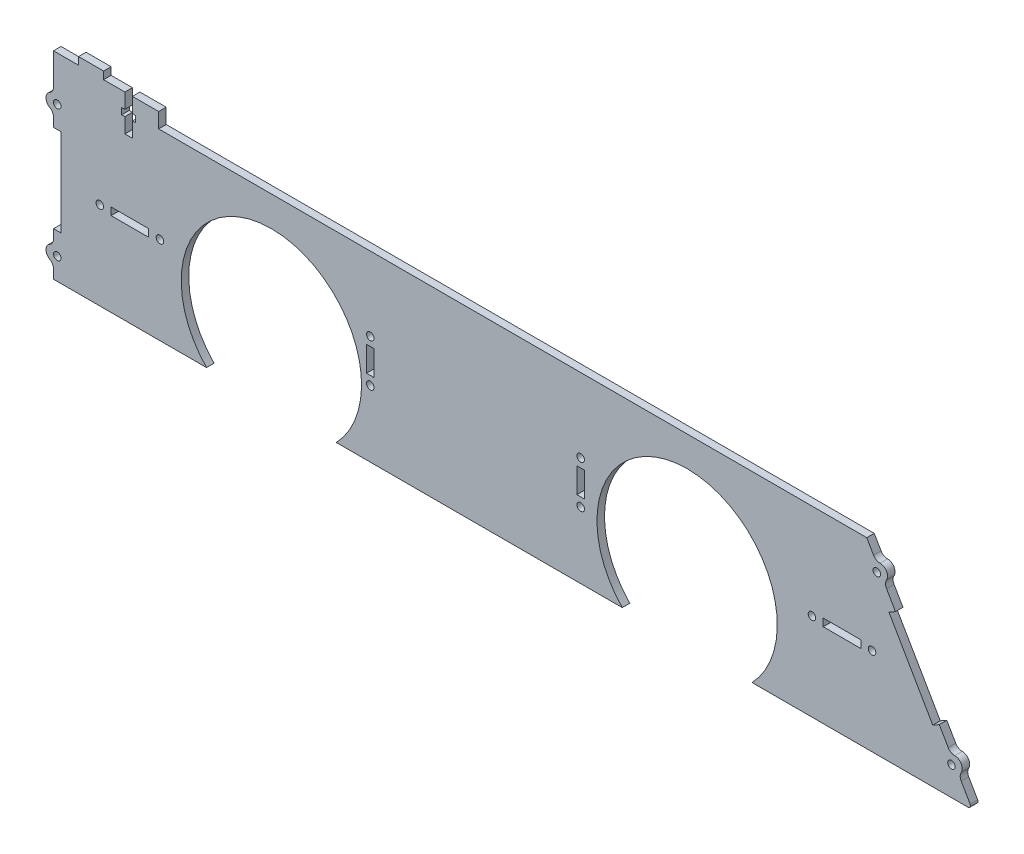
SolidWorks part; units mm, degrees
ref_plane "Спереди" through (0, 0, 0) normal (0, 0, 1) x (1, 0, 0)
ref_plane "Сверху" through (0, 0, 0) normal (0, 1, 0) x (1, 0, 0)
ref_plane "Справа" through (0, 0, 0) normal (1, 0, 0) x (0, 0, -1)
sketch "Эскиз1" plane through (0, 0, 0) normal (0, 0, 1) x (1, 0, 0)
  line L5 (-42.1466, 73) -> (0, 0)
  line L6 (-366.8766, 73) -> (-42.1466, 73)
  line L7 (-366.8766, 0) -> (-366.8766, 73)
  line L8 (0, 0) -> (-366.8766, 0)
  dimension "D1" = 60
  dimension "D2" = 73
  dimension "D3" = 324.73
  dimension "D4" = 84.2931
extrude "Бобышка-Вытянуть1" add sketch "Эскиз1" along normal blind 3
sketch "Эскиз2" plane through (0, 0, 3) normal (0, 0, 1) x (1, 0, 0)
  line L0 (-366.8766, 73) -> (-366.8766, 0) construction
  line L1 (-366.8766, 52.5) -> (-363.8766, 52.5)
  line L2 (-366.8766, 52.5) -> (-366.8766, 17.5)
  line L3 (-366.8766, 17.5) -> (-363.8766, 17.5)
  line L4 (-363.8766, 52.5) -> (-363.8766, 17.5)
  point P6 (-366.8766, 35)
  dimension "D1" = 35
  dimension "D2" = 3
  dimension "D3" = 35
extrude "Вырез-Вытянуть1" cut sketch "Эскиз2" against normal blind 3
sketch "Эскиз3" plane through (0, 0, 3) normal (0, 0, 1) x (1, 0, 0)
  line L0 (-33.2874, 51.6554) -> (-30.6893, 53.1554)
  line L1 (-33.2874, 51.6554) -> (-15.7874, 21.3446)
  line L2 (-30.6893, 53.1554) -> (-13.1893, 22.8446)
  line L3 (-15.7874, 21.3446) -> (-13.1893, 22.8446)
  line L4 (-45.6107, 73) -> (-3.4641, 0) construction
  line L5 (-42.1466, 73) -> (-366.8766, 73) construction
  line L9 (0, 0) -> (-42.1466, 73) construction
  line L10 (-366.8766, 0) -> (0, 0) construction
  line L11 (0, 0) -> (-42.1466, 73) construction
  point P12 (-24.5374, 36.5)
  point P13 (-24.5374, 36.5)
  dimension "D1" = 35
  dimension "D2" = 3
extrude "Вырез-Вытянуть2" cut sketch "Эскиз3" against normal blind 3
sketch "Эскиз4" plane through (0, 0, 3) normal (0, 0, 1) x (1, 0, 0)
  line L0 (-366.8766, 0) -> (0, 0) construction
  line L1 (-241.8766, 40) -> (-238.8766, 40)
  line L2 (-241.8766, 40) -> (-241.8766, 30)
  line L3 (-241.8766, 30) -> (-238.8766, 30)
  line L4 (-238.8766, 40) -> (-238.8766, 30)
  line L5 (-241.8766, 40) -> (-238.8766, 30) construction
  line L6 (-241.8766, 30) -> (-238.8766, 40) construction
  line L7 (-157.8766, 40) -> (-154.8766, 40)
  line L8 (-157.8766, 40) -> (-157.8766, 30)
  line L9 (-157.8766, 30) -> (-154.8766, 30)
  line L10 (-154.8766, 40) -> (-154.8766, 30)
  line L11 (-157.8766, 40) -> (-154.8766, 30) construction
  line L12 (-157.8766, 30) -> (-154.8766, 40) construction
  point P0 (-240.3766, 35)
  point P5 (-156.3766, 35)
  dimension "D1" = 3
  dimension "D2" = 10
  dimension "D3" = 84
  dimension "D4" = 123.5
  dimension "D5" = 35
extrude "Вырез-Вытянуть3" cut sketch "Эскиз4" against normal blind 3
sketch "Эскиз5" plane through (0, 0, 3) normal (0, 0, 1) x (1, 0, 0)
  line L1 (-343.8766, 36.5) -> (-328.8766, 36.5)
  line L2 (-343.8766, 36.5) -> (-343.8766, 33.5)
  line L3 (-343.8766, 33.5) -> (-328.8766, 33.5)
  line L4 (-328.8766, 36.5) -> (-328.8766, 33.5)
  line L5 (-343.8766, 36.5) -> (-328.8766, 33.5) construction
  line L6 (-343.8766, 33.5) -> (-328.8766, 36.5) construction
  line L7 (-59.5366, 36.5) -> (-44.5366, 36.5)
  line L8 (-59.5366, 36.5) -> (-59.5366, 33.5)
  line L9 (-59.5366, 33.5) -> (-44.5366, 33.5)
  line L10 (-44.5366, 36.5) -> (-44.5366, 33.5)
  line L11 (-59.5366, 36.5) -> (-44.5366, 33.5) construction
  line L12 (-59.5366, 33.5) -> (-44.5366, 36.5) construction
  point P0 (-336.3766, 35)
  point P5 (-52.0366, 35)
  dimension "D1" = 15
  dimension "D2" = 3
  dimension "D3" = 27.5
  dimension "D4" = 284.34
  dimension "D5" = 35
extrude "Вырез-Вытянуть4" cut sketch "Эскиз5" against normal blind 3
sketch "Эскиз6" plane through (0, 73, 0) normal (0, 1, 0) x (1, 0, 0)
  line L0 (-42.1466, -3) -> (-366.8766, -3) construction
  line L1 (-366.8766, 0) -> (-324.8766, 0)
  line L2 (-366.8766, 0) -> (-366.8766, -3)
  line L3 (-366.8766, -3) -> (-324.8766, -3)
  line L4 (-324.8766, 0) -> (-324.8766, -3)
  dimension "D1" = 42
extrude "Бобышка-Вытянуть2" add sketch "Эскиз6" along normal blind 6
sketch "Эскиз7" plane through (0, 0, 3) normal (0, 0, 1) x (1, 0, 0)
  line L0 (-366.8766, 17.5) -> (-366.8766, 0) construction
  line L1 (-363.8766, 35) -> (-385.1167, 35) construction
  line L2 (-363.8766, 17.5) -> (-363.8766, 52.5) construction
  circle A0 centre (-365.3766, 8.75) radius 1.5
  circle A1 centre (-365.3766, 61.25) radius 1.5
  point P5 (-366.8766, 8.75)
  dimension "D1" = 3
  dimension "D2" = 1.5
sketch "Эскиз8" plane through (-366.8766, 0, 0) normal (-1, 0, 0) x (0, 0, 1)
  line L0 (0, 17.5) -> (0, 0) construction
  line L1 (0, 8.75) -> (3, 8.75)
  line L2 (0, 8.75) -> (0, 5.75)
  line L3 (0, 5.75) -> (3, 5.75)
  line L4 (3, 8.75) -> (3, 5.75)
  line L5 (3, 17.5) -> (3, 0) construction
  dimension "D1" = 3
revolve "Повернуть1" add sketch "Эскиз8" angle 360 about L1
sketch "Эскиз9" plane through (-366.8766, 0, 0) normal (-1, 0, 0) x (0, 0, 1)
  line L0 (0, 79) -> (0, 52.5) construction
  line L1 (0, 61.25) -> (3, 61.25)
  line L2 (0, 61.25) -> (0, 58.25)
  line L3 (0, 58.25) -> (3, 58.25)
  line L4 (3, 61.25) -> (3, 58.25)
  line L5 (3, 79) -> (3, 52.5) construction
  dimension "D1" = 3
  dimension "D2" = 8.75
revolve "Повернуть2" add sketch "Эскиз9" angle 360 about L1
extrude "Вырез-Вытянуть6" cut sketch "Эскиз7" against normal blind 3
fillet "Скругление1" radius 3 4 edges at (-366.8766, 5.75, 1.5) (-366.8766, 11.75, 1.5) (-366.8766, 58.25, 1.5) (-366.8766, 64.25, 1.5)
sketch "Эскиз14" plane through (0, 0, 3) normal (0, 0, 1) x (1, 0, 0)
  line L0 (-154.8766, 40) -> (-157.8766, 40) construction
  line L1 (-157.8766, 30) -> (-154.8766, 30) construction
  line L2 (-241.8766, 30) -> (-238.8766, 30) construction
  circle A0 centre (-156.3766, 43.5) radius 1.5
  circle A1 centre (-156.3766, 26.5) radius 1.5
  circle A2 centre (-240.3766, 26.5) radius 1.5
  circle A3 centre (-240.3766, 43.5) radius 1.5
  point P11 (-156.3766, 40)
  point P20 (-240.3766, 30)
  dimension "D1" = 3
  dimension "D2" = 3.5
  dimension "D3" = 3.5
extrude "Вырез-Вытянуть9" cut sketch "Эскиз14" against normal blind 3
sketch "Эскиз15" plane through (0, 0, 3) normal (0, 0, 1) x (1, 0, 0)
  line L0 (-59.5366, 36.5) -> (-59.5366, 33.5) construction
  line L1 (-44.5366, 33.5) -> (-44.5366, 36.5) construction
  line L2 (-343.8766, 36.5) -> (-343.8766, 33.5) construction
  line L3 (-328.8766, 33.5) -> (-328.8766, 36.5) construction
  circle A0 centre (-324.3766, 35) radius 1.5
  circle A1 centre (-348.3766, 35) radius 1.5
  circle A2 centre (-64.0366, 35) radius 1.5
  circle A3 centre (-40.0366, 35) radius 1.5
  point P16 (-59.5366, 35)
  dimension "D1" = 3
  dimension "D2" = 4.5
  dimension "D3" = 4.5
  dimension "D4" = 4.5
  dimension "D5" = 4.5
extrude "Вырез-Вытянуть10" cut sketch "Эскиз15" against normal blind 3
sketch "Эскиз16" plane through (0, 0, 0) normal (0.866, 0.5, 0) x (0, 0, -1)
  line L0 (-3, 0) -> (-3, 26.3786) construction
  line L1 (-3, 11.0586) -> (0, 11.0586)
  line L2 (-3, 11.0586) -> (-3, 14.0586)
  line L3 (-3, 14.0586) -> (0, 14.0586)
  line L4 (0, 11.0586) -> (0, 14.0586)
  line L5 (0, 0) -> (0, 26.3786) construction
  dimension "D1" = 3
  dimension "D2" = 12.32
revolve "Повернуть3" add sketch "Эскиз16" angle 360 about L3
sketch "Эскиз17" plane through (0, 0, 0) normal (0.866, 0.5, 0) x (0, 0, -1)
  line L0 (-3, 61.3786) -> (-3, 84.2931) construction
  line L1 (-3, 73.6986) -> (0, 73.6986)
  line L2 (-3, 73.6986) -> (-3, 76.6986)
  line L3 (-3, 76.6986) -> (0, 76.6986)
  line L4 (0, 73.6986) -> (0, 76.6986)
  line L5 (0, 61.3786) -> (0, 84.2931) construction
  dimension "D1" = 3
  dimension "D2" = 12.32
revolve "Повернуть4" add sketch "Эскиз17" angle 360 about L1
sketch "Эскиз18" plane through (0, 0, 3) normal (0, 0, 1) x (1, 0, 0)
  line L0 (-33.2874, 51.6554) -> (-45.6107, 73) construction
  line L1 (-15.7874, 21.3446) -> (-3.4641, 0) construction
  line L2 (0, 0) -> (-5.5293, 9.577) construction
  line L3 (-366.8766, 0) -> (0, 0) construction
  line L4 (-42.1466, 73) -> (-324.8766, 73) construction
  line L5 (-9.6257, 10.6723) -> (-6.0018, 12.7646) construction
  line L7 (-38.3493, 66.423) -> (-42.1466, 73) construction
  line L8 (-39.449, 62.3277) -> (-36.7928, 63.8613) construction
  circle A0 centre (-38.15, 63.0777) radius 1.5
  circle A1 centre (-8.3267, 11.4223) radius 1.5
  dimension "D1" = 3
  dimension "D2" = 3
  dimension "D3" = 1.5
  dimension "D4" = 1.5
extrude "Вырез-Вытянуть11" cut sketch "Эскиз18" against normal blind 3
fillet "Скругление2" radius 3 4 edges at (-35.3493, 61.2268, 1.5) (-38.3493, 66.423, 1.5) (-5.5293, 9.577, 1.5) (-8.5293, 14.7732, 1.5)
sketch "Эскиз19" plane through (0, 0, 3) normal (0, 0, 1) x (1, 0, 0)
  line L0 (-366.8766, 0) -> (0, 0) construction
  line L1 (-363.8766, 17.5) -> (-363.8766, 52.5) construction
  circle A0 centre (-279.8766, 25) radius 36
  circle A1 centre (-113.8766, 25) radius 36
  dimension "D1" = 25
  dimension "D3" = 166
  dimension "D4" = 72
  dimension "D2" = 84
extrude "Вырез-Вытянуть12" cut sketch "Эскиз19" against normal blind 3
sketch "Эскиз20" plane through (0, 0, 3) normal (0, 0, 1) x (1, 0, 0)
  line L0 (-338.3766, 79) -> (-338.3766, 73)
  line L1 (-338.3766, 73) -> (-339.6266, 73)
  line L2 (-339.6266, 73) -> (-339.6266, 70.5)
  line L3 (-339.6266, 70.5) -> (-338.3766, 70.5)
  line L4 (-338.3766, 70.5) -> (-338.3766, 64.5)
  line L5 (-338.3766, 64.5) -> (-335.3766, 64.5)
  line L6 (-335.3766, 64.5) -> (-335.3766, 70.5)
  line L7 (-335.3766, 70.5) -> (-334.1266, 70.5)
  line L8 (-334.1266, 70.5) -> (-334.1266, 73)
  line L9 (-334.1266, 73) -> (-335.3766, 73)
  line L10 (-335.3766, 73) -> (-335.3766, 79)
  line L11 (-335.3766, 79) -> (-338.3766, 79)
  line L12 (-366.8766, 79) -> (-324.8766, 79) construction
  point P16 (-336.8766, 79)
  dimension "D1" = 3
  dimension "D2" = 5.5
  dimension "D3" = 6
  dimension "D4" = 2.5
  dimension "D5" = 30
extrude "Вырез-Вытянуть13" cut sketch "Эскиз20" against normal blind 3
sketch "Эскиз21" plane through (0, 79, 0) normal (0, 1, 0) x (1, 0, 0)
  line L0 (-366.8766, -3) -> (-338.3766, -3) construction
  line L1 (-356.8766, -3) -> (-346.8766, -3)
  line L2 (-356.8766, -3) -> (-356.8766, 0)
  line L3 (-356.8766, 0) -> (-346.8766, 0)
  line L4 (-346.8766, -3) -> (-346.8766, 0)
  line L5 (-338.3766, 0) -> (-366.8766, 0) construction
  dimension "D1" = 10
  dimension "D2" = 10
extrude "Бобышка-Вытянуть3" add sketch "Эскиз21" along normal blind 3
fillet "Скругление3" radius 1 1 edges at (0, 0, 1.5)
